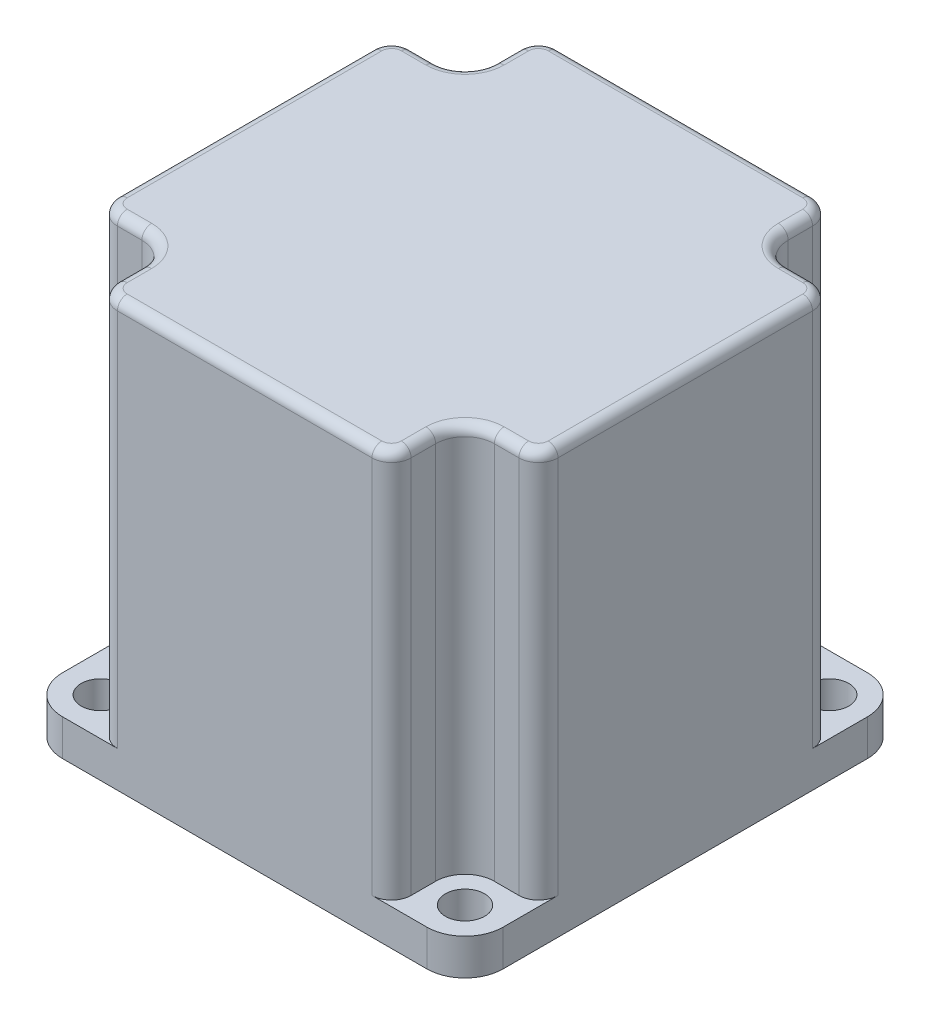
SolidWorks part; units mm, degrees
material "Plain Carbon Steel"
ref_plane "Front Plane" through (0, 0, 0) normal (0, 0, 1) x (1, 0, 0)
ref_plane "Top Plane" through (0, 0, 0) normal (0, 1, 0) x (1, 0, 0)
ref_plane "Right Plane" through (0, 0, 0) normal (1, 0, 0) x (0, 0, -1)
sketch "Sketch1" plane through (0, 0, 0) normal (0, 1, 0) x (1, 0, 0)
  line L0 (0, 28.575) -> (0, -28.575) construction
  line L1 (-23.622, 28.575) -> (23.622, 28.575)
  line L2 (-28.575, 23.622) -> (-28.575, -23.622)
  line L3 (-23.622, -28.575) -> (23.622, -28.575)
  line L4 (28.575, 23.622) -> (28.575, -23.622)
  line L6 (23.622, -23.622) -> (-23.622, -23.622) construction
  line L7 (23.622, -23.622) -> (23.622, 23.622) construction
  line L8 (23.622, 23.622) -> (-23.622, 23.622) construction
  line L9 (-23.622, -23.622) -> (-23.622, 23.622) construction
  line L11 (23.622, 23.622) -> (-23.622, -23.622) construction
  circle A0 centre (-23.622, 23.622) radius 2.54
  circle A1 centre (23.622, 23.622) radius 2.54
  circle A2 centre (23.622, -23.622) radius 2.54
  circle A3 centre (-23.622, -23.622) radius 2.54
  arc A4 (-28.575, -23.622) -> (-23.622, -28.575) centre (-23.622, -23.622) ccw
  arc A5 (23.622, -28.575) -> (28.575, -23.622) centre (23.622, -23.622) ccw
  arc A6 (23.622, 28.575) -> (28.575, 23.622) centre (23.622, 23.622) cw
  arc A7 (-23.622, 28.575) -> (-28.575, 23.622) centre (-23.622, 23.622) ccw
  point P6 (0, 0)
  dimension "D3" = 5.08
  dimension "D1" = 57.15
  dimension "D2" = 47.244
extrude "Boss-Extrude1" add sketch "Sketch1" along normal blind 4.699
sketch "Sketch2" plane through (0, 4.699, 0) normal (0, 1, 0) x (1, 0, 0)
  line L0 (-19.05, -28.575) -> (-19.05, -19.05)
  line L1 (-23.622, -28.575) -> (23.622, -28.575) construction
  line L2 (-19.05, -19.05) -> (-28.575, -19.05)
  line L3 (-28.575, 23.622) -> (-28.575, -23.622) construction
  line L4 (-28.575, -19.05) -> (-28.575, 19.05)
  line L5 (-28.575, 19.05) -> (-19.05, 19.05)
  line L6 (-19.05, 19.05) -> (-19.05, 28.575)
  line L7 (23.622, 28.575) -> (-23.622, 28.575) construction
  line L8 (-19.05, 28.575) -> (19.05, 28.575)
  line L9 (19.05, 28.575) -> (19.05, 19.05)
  line L10 (19.05, 19.05) -> (28.575, 19.05)
  line L11 (28.575, -23.622) -> (28.575, 23.622) construction
  line L12 (28.575, 19.05) -> (28.575, -19.05)
  line L13 (28.575, -19.05) -> (19.05, -19.05)
  line L14 (19.05, -19.05) -> (19.05, -28.575)
  line L15 (19.05, -28.575) -> (-19.05, -28.575)
  dimension "D1" = 38.1
extrude "Boss-Extrude2" add sketch "Sketch2" along normal blind 50.419
fillet "Fillet1" radius 3.81 4 edges at (-19.05, 29.9085, 19.05) (-19.05, 29.9085, -19.05) (19.05, 29.9085, -19.05) (19.05, 29.9085, 19.05)
fillet "Fillet2" radius 2.54 8 edges
fillet "Fillet3" radius 1.27 24 edges at (27.8311, 55.118, 18.3061) (24.4475, 55.118, 19.05) (20.1659, 55.118, 20.1659) (19.05, 55.118, 24.4475) (18.3061, 55.118, 27.8311) (0, 55.118, 28.575) (-18.3061, 55.118, 27.8311) (-19.05, 55.118, 24.4475) (-20.1659, 55.118, 20.1659) (-24.4475, 55.118, 19.05) (-27.8311, 55.118, 18.3061) (-28.575, 55.118, 0) (-27.8311, 55.118, -18.3061) (-24.4475, 55.118, -19.05) (-20.1659, 55.118, -20.1659) (-19.05, 55.118, -24.4475) (-18.3061, 55.118, -27.8311) (0, 55.118, -28.575) (18.3061, 55.118, -27.8311) (19.05, 55.118, -24.4475) (20.1659, 55.118, -20.1659) (24.4475, 55.118, -19.05) (27.8311, 55.118, -18.3061) (28.575, 55.118, 0)
sketch "Sketch3" plane through (0, 0, 0) normal (0, -1, 0) x (1, 0, 0)
  circle A0 centre (0, 0) radius 19.05
  dimension "D1" = 38.1
extrude "Boss-Extrude3" add sketch "Sketch3" along normal blind 1.524
sketch "Sketch4" plane through (0, -1.524, 0) normal (0, -1, 0) x (1, 0, 0)
  circle A0 centre (0, 0) radius 3.175
  dimension "D1" = 6.35
sketch "Sketch5" plane through (0, 0, 0) normal (0, -1, 0) x (1, 0, 0)
  circle A0 centre (0, 0) radius 22.225
  dimension "D1" = 44.45
extrude "Cut-Extrude1" cut sketch "Sketch5" against normal blind 44.45 from offset 6.35 offset against normal yes
extrude "Boss-Extrude4" add sketch "Sketch4" along normal blind 19.05
